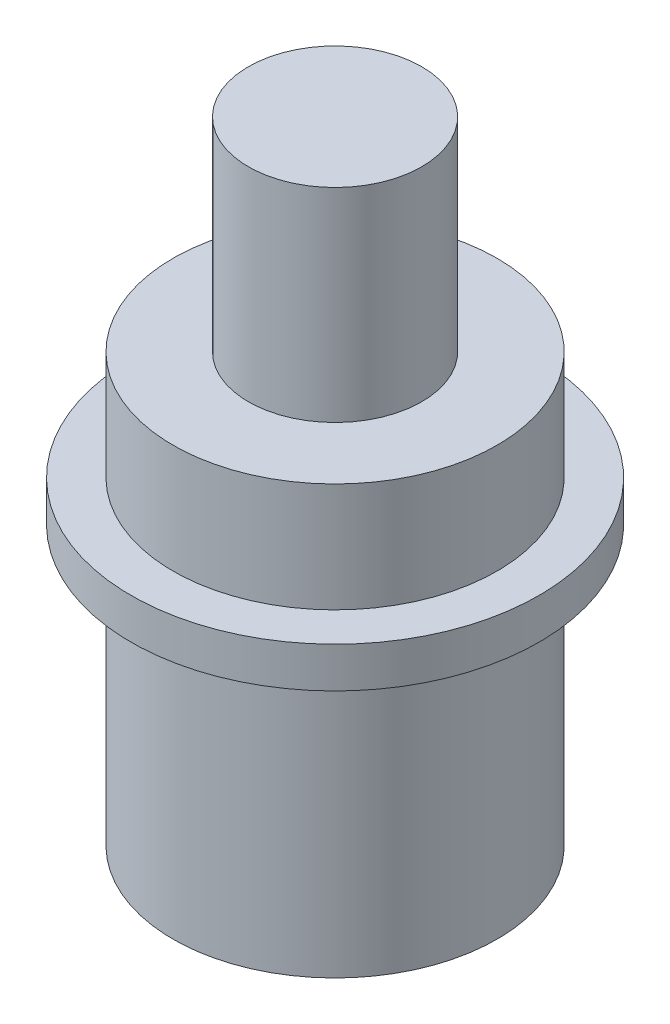
SolidWorks part; units mm, degrees
material "黄铜"
ref_plane "前视基准面" through (0, 0, 0) normal (0, 0, 1) x (1, 0, 0)
ref_plane "上视基准面" through (0, 0, 0) normal (0, 1, 0) x (1, 0, 0)
ref_plane "右视基准面" through (0, 0, 0) normal (1, 0, 0) x (0, 0, -1)
sketch "草图1" plane through (0, 0, 0) normal (0, 0, 1) x (1, 0, 0)
  line L0 (0, 0) -> (0, 19.2962) construction
  line L1 (0, 0) -> (3.12, 0)
  line L2 (3.12, 0) -> (3.12, 5.36)
  line L3 (3.12, 5.36) -> (3.93, 5.36)
  line L4 (3.93, 5.36) -> (3.93, 6.14)
  line L5 (3.93, 6.14) -> (3.12, 6.14)
  line L6 (3.12, 6.14) -> (3.12, 8.24)
  line L7 (3.12, 8.24) -> (1.67, 8.24)
  line L8 (1.67, 8.24) -> (1.67, 12.16)
  line L9 (1.67, 12.16) -> (0, 12.16)
  line L10 (0, 12.16) -> (0, 0)
  dimension "D1" = 12.16
  dimension "D2" = 1.67
  dimension "D3" = 8.24
  dimension "D4" = 6.14
  dimension "D5" = 0.78
  dimension "D6" = 3.12
  dimension "D7" = 3.93
revolve "旋转1" add sketch "草图1" angle 360 about L0
cosmetic thread "装饰螺纹线3" parameters "D2"=2.459
sketch "草图2" plane through (0, 0, 0) normal (0, -1, 0) x (1, 0, 0)
  circle A0 centre (0, 0) radius 1.67
  dimension "D1" = 3.34
extrude "切除-拉伸1" cut sketch "草图2" against normal blind 4.02
cosmetic thread "装饰螺纹线2" parameters "D2"=5
sketch "草图3" plane through (0, 0, 0) normal (0, 0, 1) x (1, 0, 0)
  line L0 (2.62, 0) -> (1.67, 0.95)
  line L1 (-3.12, 0) -> (3.12, 0) construction
  line L2 (1.67, 0.95) -> (0, 0.95)
  line L3 (0, 0.95) -> (0, 0)
  line L4 (0, 0) -> (2.62, 0)
  dimension "D1" = 1.67
  dimension "D2" = 2.62
  dimension "D3" = 45
revolve "切除-旋转1" cut sketch "草图3" angle 360 about axis through (0, 0, 0) along (0, -1, 0)
